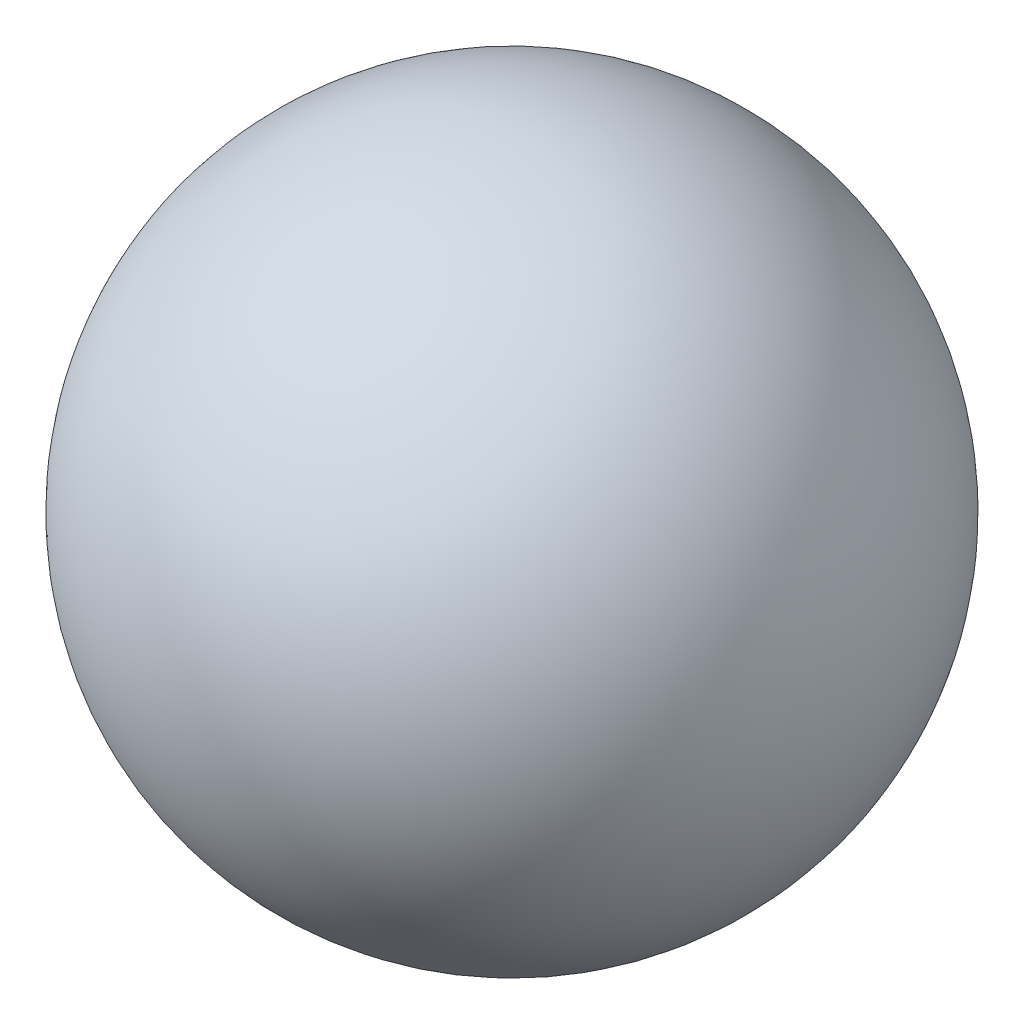
SolidWorks part; units mm, degrees
ref_plane "Front Plane" through (0, 0, 0) normal (0, 0, 1) x (1, 0, 0)
ref_plane "Top Plane" through (0, 0, 0) normal (0, 1, 0) x (1, 0, 0)
ref_plane "Right Plane" through (0, 0, 0) normal (1, 0, 0) x (0, 0, -1)
sketch "Sketch1" plane through (0, 0, 0) normal (0, 0, 1) x (1, 0, 0)
  line L0 (-11.3587, 0) -> (12.6413, 0)
  arc A0 (12.6413, 0) -> (-11.3587, 0) centre (0.6413, 0) cw
  dimension "D1" = 24
revolve "Revolve1" add sketch "Sketch1" angle 360 about L0
